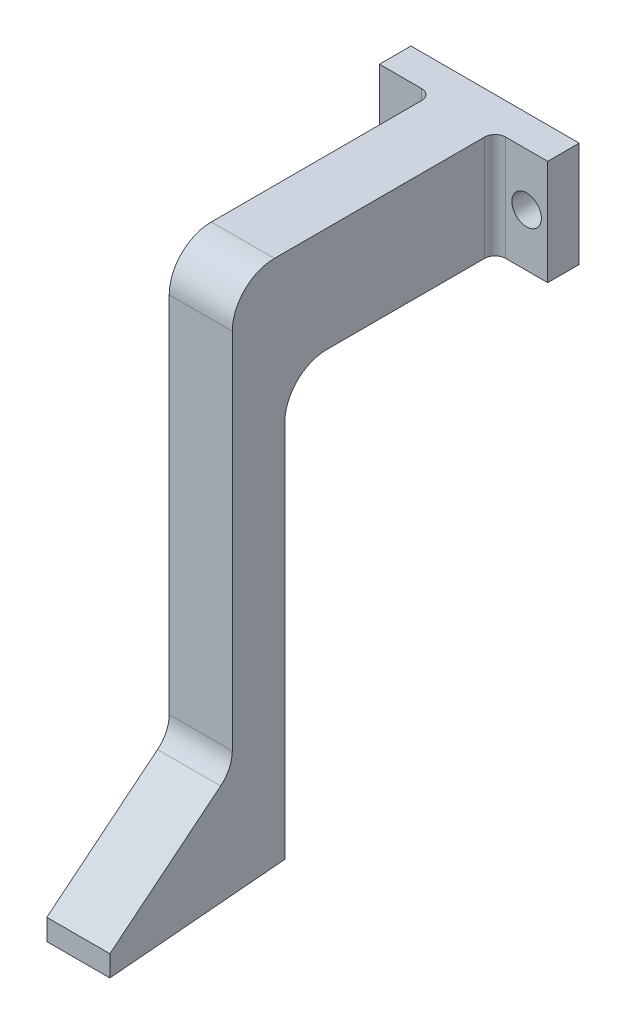
SolidWorks part; units mm, degrees
material "ABS"
ref_plane "Front Plane" through (0, 0, 0) normal (0, 0, 1) x (1, 0, 0)
ref_plane "Top Plane" through (0, 0, 0) normal (0, 1, 0) x (1, 0, 0)
ref_plane "Right Plane" through (0, 0, 0) normal (1, 0, 0) x (0, 0, -1)
sketch "Sketch3" plane through (0, 0, 0) normal (0, 0, 1) x (1, 0, 0)
  line L1 (-10.16, 6.35) -> (10.16, 6.35)
  line L2 (-10.16, 6.35) -> (-10.16, -6.35)
  line L3 (-10.16, -6.35) -> (10.16, -6.35)
  line L4 (10.16, 6.35) -> (10.16, -6.35)
  line L5 (-10.16, 6.35) -> (10.16, -6.35) construction
  line L6 (-10.16, -6.35) -> (10.16, 6.35) construction
  point P0 (0, 0)
  dimension "D1" = 20.32
  dimension "D2" = 12.7
extrude "Boss-Extrude1" add sketch "Sketch3" along normal blind 3.81
sketch "Sketch4" plane through (0, 0, 3.81) normal (0, 0, 1) x (1, 0, 0)
  line L0 (10.16, 6.35) -> (-10.16, 6.35) construction
  circle A0 centre (-7.62, 0) radius 1.778
  circle A1 centre (7.62, 0) radius 1.778
  dimension "D1" = 3.556
  dimension "D2" = 3.556
  dimension "D3" = 6.35
  dimension "D4" = 6.35
  dimension "D5" = 7.62
  dimension "D6" = 7.62
extrude "Cut-Extrude1" cut sketch "Sketch4" against normal blind 3.81 contours A1 | A0
sketch "Sketch5" plane through (0, 0, 3.81) normal (0, 0, 1) x (1, 0, 0)
  line L1 (-3.81, -6.35) -> (3.81, -6.35)
  line L2 (-3.81, -6.35) -> (-3.81, 6.35)
  line L3 (-3.81, 6.35) -> (3.81, 6.35)
  line L4 (3.81, -6.35) -> (3.81, 6.35)
  line L5 (-3.81, -6.35) -> (3.81, 6.35) construction
  line L6 (-3.81, 6.35) -> (3.81, -6.35) construction
  point P0 (0, 0)
  dimension "D1" = 12.7
  dimension "D2" = 7.62
extrude "Boss-Extrude2" add sketch "Sketch5" along normal blind 25.4
fillet "Fillet1" radius 1.27 1 edges at (-3.81, 0, 3.81)
fillet "Fillet2" radius 1.27 1 edges at (3.81, 0, 3.81)
sketch "Sketch10" plane through (-3.81, 0, 0) normal (-1, 0, 0) x (0, 0, 1)
  line L0 (29.21, 6.35) -> (29.21, -57.15)
  line L2 (29.21, -57.15) -> (50.3478, -58.9993)
  line L3 (50.3478, -58.9993) -> (50.3478, -56.4593)
  line L4 (50.3478, -56.4593) -> (35.56, -44.45)
  line L5 (35.56, -44.45) -> (35.56, 6.35)
  line L6 (35.56, 6.35) -> (29.21, 6.35)
  dimension "D1" = 63.5
  dimension "D2" = 95
  dimension "D3" = 19.05
  dimension "D4" = 50.8
  dimension "D5" = 2.54
  dimension "D6" = 6.35
extrude "Boss-Extrude6" add sketch "Sketch10" against normal blind 7.62
fillet "Fillet5" radius 5.08 1 edges at (0, -6.35, 29.21)
fillet "Fillet6" radius 5.08 1 edges at (0, 6.35, 35.56)
fillet "Fillet7" radius 3.81 1 edges at (0, -44.45, 35.56)
